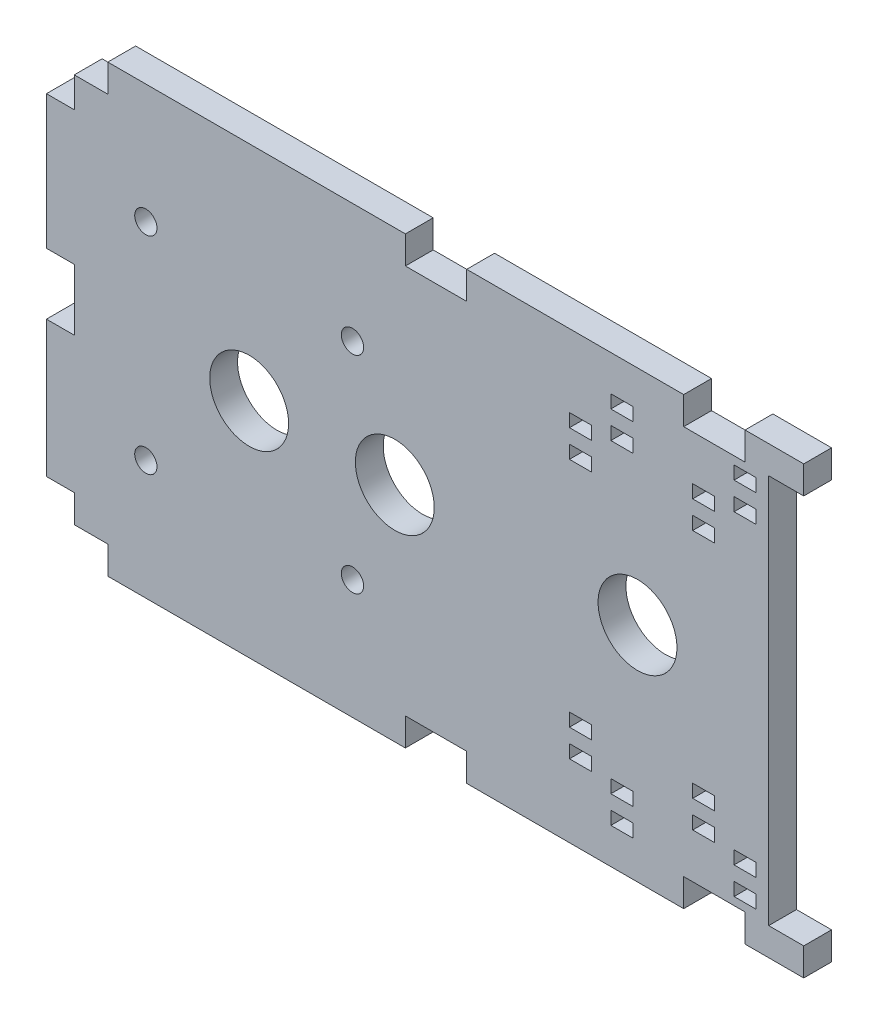
SolidWorks part; units mm, degrees
ref_plane "Front Plane" through (0, 0, 0) normal (0, 0, 1) x (1, 0, 0)
ref_plane "Top Plane" through (0, 0, 0) normal (0, 1, 0) x (1, 0, 0)
ref_plane "Right Plane" through (0, 0, 0) normal (1, 0, 0) x (0, 0, -1)
sketch "Sketch2" plane through (0, 0, 0) normal (0, 0, 1) x (1, 0, 0)
  line L1 (-88.9, -50.8) -> (88.9, -50.8)
  line L2 (-88.9, -50.8) -> (-88.9, 50.8)
  line L3 (-88.9, 50.8) -> (88.9, 50.8)
  line L4 (88.9, -50.8) -> (88.9, 50.8)
  line L5 (-88.9, -50.8) -> (88.9, 50.8) construction
  line L6 (-88.9, 50.8) -> (88.9, -50.8) construction
  point P0 (0, 0)
  dimension "D1" = 101.6
  dimension "D2" = 177.8
extrude "Boss-Extrude3" add sketch "Sketch2" along normal blind 6.35
sketch "Sketch3" plane through (0, 0, 6.35) normal (0, 0, 1) x (1, 0, 0)
  line L0 (-88.9, 0) -> (0, 0) construction
  line L1 (-88.9, 50.8) -> (-88.9, -50.8) construction
  line L2 (0, 0) -> (88.9, 0) construction
  line L3 (88.9, -50.8) -> (88.9, 50.8) construction
  line L4 (0, 50.8) -> (0, -50.8) construction
  line L5 (88.9, 50.8) -> (-88.9, 50.8) construction
  line L6 (-88.9, -50.8) -> (88.9, -50.8) construction
  line L7 (-9.4121, 0) -> (-42.6438, 0) construction
  line L8 (45.9739, 0) -> (-9.4121, 0) construction
  line L9 (-51.6438, 0) -> (-42.6438, -9)
  line L10 (-42.6438, -9) -> (-33.6438, 0)
  line L11 (-33.6438, 0) -> (-42.6438, 9)
  line L12 (-42.6438, 9) -> (-51.6438, 0)
  line L21 (-66.2169, -23.5732) -> (-19.0706, -23.5732)
  line L22 (-66.2169, -23.5732) -> (-66.2169, 23.5732)
  line L23 (-66.2169, 23.5732) -> (-19.0706, 23.5732)
  line L24 (-19.0706, -23.5732) -> (-19.0706, 23.5732)
  line L25 (-66.2169, -23.5732) -> (-19.0706, 23.5732) construction
  line L26 (-66.2169, 23.5732) -> (-19.0706, -23.5732) construction
  line L29 (26.7151, -50.8) -> (26.7151, 50.8) construction
  line L30 (-66.2169, 23.5732) -> (-66.2169, 26.1132) construction
  circle A1 centre (-9.4121, 0) radius 9
  circle A2 centre (-42.6438, 0) radius 9
  circle A3 centre (-66.2169, 23.5732) radius 2.54
  circle A4 centre (-19.0706, 23.5732) radius 2.54
  circle A5 centre (-66.2169, -23.5732) radius 2.54
  circle A6 centre (-19.0706, -23.5732) radius 2.54
  circle A7 centre (45.9739, 0) radius 9
  dimension "D1" = 18
  dimension "D2" = 18
  dimension "D3" = 18
  dimension "D5" = 55.386
  dimension "D6" = 33.2317
  dimension "D7" = 46.2563
extrude "Cut-Extrude1" cut sketch "Sketch3" against normal through all contours A3 | A6 | A5 | A1 | A7 | A2 | A4
sketch "Sketch7" plane through (0, 0, 6.35) normal (0, 0, 1) x (1, 0, 0)
  line L0 (-19.0706, 26.1132) -> (-19.0706, 50.8) construction
  line L1 (88.9, 50.8) -> (-88.9, 50.8) construction
  line L2 (-64.4709, 21.7285) -> (-88.9, 21.7285) construction
  line L3 (-88.9, 50.8) -> (-88.9, -50.8) construction
  line L4 (-88.9, -7) -> (-88.9, 7)
  line L5 (-88.9, 50.8) -> (-74.9, 50.8)
  line L6 (-88.9, 50.8) -> (-88.9, 44.45)
  line L7 (-74.9, 44.45) -> (-82.55, 44.45)
  line L8 (-74.9, 50.8) -> (-74.9, 44.45)
  line L9 (-88.9, -50.8) -> (-74.9, -50.8)
  line L10 (-88.9, -50.8) -> (-88.9, -44.45)
  line L11 (-74.9, -44.45) -> (-82.55, -44.45)
  line L12 (-74.9, -50.8) -> (-74.9, -44.45)
  line L13 (-88.9, -7) -> (-82.55, -7)
  line L14 (-88.9, 7) -> (-82.55, 7)
  line L15 (-82.55, -7) -> (-82.55, 7)
  line L16 (88.9, -50.8) -> (88.9, 50.8) construction
  line L17 (7, 44.45) -> (-7, 44.45)
  line L18 (7, 44.45) -> (7, 50.8)
  line L19 (7, 50.8) -> (-7, 50.8)
  line L20 (-7, 44.45) -> (-7, 50.8)
  line L21 (70.509, 50.8) -> (70.509, 44.45)
  line L22 (83.9, 50.8) -> (83.9, -50.8)
  line L23 (7, -50.8) -> (56.509, -50.8)
  line L24 (56.509, -50.8) -> (70.509, -50.8)
  line L25 (56.509, -50.8) -> (56.509, -44.45)
  line L26 (56.509, -44.45) -> (70.509, -44.45)
  line L27 (70.509, -50.8) -> (70.509, -44.45)
  line L28 (56.509, 44.45) -> (70.509, 44.45)
  line L29 (56.509, 50.8) -> (56.509, 44.45)
  line L30 (56.509, 50.8) -> (70.509, 50.8)
  line L31 (7, 50.8) -> (56.509, 50.8)
  line L32 (83.9, -50.8) -> (88.9, -50.8)
  line L33 (-88.9, -50.8) -> (88.9, -50.8) construction
  line L34 (7, -50.8) -> (-7, -50.8)
  line L35 (7, -50.8) -> (7, -44.45)
  line L36 (-7, -50.8) -> (-7, -44.45)
  line L37 (7, -44.45) -> (-7, -44.45)
  line L38 (-88.9, -7) -> (-88.9, -44.45) construction
  line L39 (88.9, -50.8) -> (88.9, 50.8)
  line L40 (-88.9, -7) -> (-82.55, 7) construction
  line L41 (88.9, 50.8) -> (83.9, 50.8)
  line L42 (83.9, 31.875) -> (75.9, 31.875)
  line L43 (0, 0) -> (-88.9, 0) construction
  line L44 (-82.55, -7) -> (-88.9, 7) construction
  line L45 (75.9, 50.8) -> (75.9, -50.8)
  line L46 (-88.9, 0) -> (88.9, 0) construction
  line L47 (0, 50.8) -> (0, -50.8) construction
  line L48 (0, 50.8) -> (0, 44.45) construction
  line L49 (0, -44.45) -> (0, -50.8) construction
  line L50 (-82.55, 44.45) -> (-82.55, 37.5545)
  line L51 (-82.55, 37.5545) -> (-88.9, 37.5545)
  line L52 (-88.9, 44.45) -> (-88.9, 37.5545)
  line L53 (83.9, 44.45) -> (75.9, 44.45)
  line L54 (-82.55, -44.45) -> (-82.55, -38.1)
  line L55 (-82.55, -38.1) -> (-88.9, -38.1)
  line L56 (-88.9, -44.45) -> (-88.9, -38.1)
  line L57 (75.9, -44.45) -> (83.9, -44.45)
  line L58 (88.9, 16.3459) -> (83.9, 16.3459)
  circle A0 centre (-19.0706, 23.5732) radius 2.54 construction
  circle A2 centre (-66.2169, 23.5732) radius 2.54 construction
  line M8 (88.9, -50.8) -> (88.9, 50.8)
  line M9 (88.9, 50.8) -> (-88.9, 50.8)
  line M10 (-88.9, 50.8) -> (-88.9, -50.8)
  line M11 (-88.9, -50.8) -> (88.9, -50.8)
  dimension "D1" = 24.6868
  dimension "D2" = 24.4291
  dimension "D5" = 6.35
  dimension "D6" = 6.35
  dimension "D7" = 6.35
  dimension "D8" = 49.509
  dimension "D9" = 18.391
extrude "Cut-Extrude2" cut sketch "Sketch7" against normal through all contours L51 L50 L7 L8 M9 M10 | L13 L15 L14 M10 | L54 L55 L12 L11 M10 M11 | L35 L37 L36 M11 | L27 L26 L25 M11 | L29 L28 L21 M9 | L20 L17 L18 M9 | L22 M9 M11 M8 | L42 L45 L22 M11 | L45 L42 L22 M9 | L58 L22 M8 M11
sketch "Sketch9" plane through (0, 0, 6.35) normal (0, 0, 1) x (1, 0, 0)
  line L0 (68.009, -33.397) -> (68.009, -36.397)
  line L1 (39.8884, -33.397) -> (35.4434, -33.397) construction
  line L2 (30.4434, -24.965) -> (30.4434, -27.965)
  line L3 (30.4434, -34.215) -> (35.4434, -34.215)
  line L4 (35.4434, -24.965) -> (35.4434, -27.965)
  line L5 (44.8884, 38.022) -> (39.8884, 38.022) construction
  line L6 (35.4434, -34.215) -> (35.4434, -31.215)
  line L7 (35.4434, -24.965) -> (30.4434, -24.965)
  line L8 (30.4434, -27.965) -> (35.4434, -27.965)
  line L9 (30.4434, -31.215) -> (35.4434, -31.215)
  line L10 (30.4434, -27.965) -> (30.4434, -29.59)
  line L11 (30.4434, -34.215) -> (30.4434, -31.215)
  line L12 (30.4434, -29.59) -> (30.4434, -31.215)
  line L13 (35.4434, -27.965) -> (35.4434, -31.215) construction
  line L14 (35.4434, -31.215) -> (35.498, -31.0212) construction
  line L15 (35.4434, -29.59) -> (58.5634, -29.59) construction
  line L16 (58.5634, -24.965) -> (58.5634, -27.965)
  line L17 (58.5634, -34.215) -> (63.5634, -34.215)
  line L18 (63.5634, -24.965) -> (63.5634, -27.965)
  line L19 (63.5634, -34.215) -> (63.5634, -31.215)
  line L20 (63.5634, -24.965) -> (58.5634, -24.965)
  line L21 (58.5634, -27.965) -> (63.5634, -27.965)
  line L22 (58.5634, -31.215) -> (63.5634, -31.215)
  line L23 (58.5634, -27.965) -> (58.5634, -29.59)
  line L24 (58.5634, -34.215) -> (58.5634, -31.215)
  line L25 (58.5634, -29.59) -> (58.5634, -31.215)
  line L26 (63.5634, -27.965) -> (63.5634, -31.215) construction
  line L27 (63.5634, -31.215) -> (63.618, -31.0212) construction
  line L28 (63.5634, -29.59) -> (58.5634, -29.59) construction
  line L29 (39.8884, 33.397) -> (35.4434, 33.397) construction
  line L30 (63.5629, 29.59) -> (83.9, 29.59) construction
  line L31 (63.5629, 31.215) -> (63.6175, 31.0212) construction
  line L32 (63.5629, 27.965) -> (63.5629, 31.215) construction
  line L33 (35.4429, 29.59) -> (58.5629, 29.59) construction
  line L34 (35.4434, 31.215) -> (35.498, 31.0212) construction
  line L35 (35.4434, 27.965) -> (35.4434, 31.215) construction
  line L36 (58.5629, 29.59) -> (58.5629, 31.215)
  line L37 (58.5629, 34.215) -> (58.5629, 31.215)
  line L38 (58.5629, 27.965) -> (58.5629, 29.59)
  line L39 (58.5629, 31.215) -> (63.5629, 31.215)
  line L40 (58.5629, 27.965) -> (63.5629, 27.965)
  line L41 (63.5629, 24.965) -> (58.5629, 24.965)
  line L42 (63.5629, 34.215) -> (63.5629, 31.215)
  line L43 (63.5629, 24.965) -> (63.5629, 27.965)
  line L44 (58.5629, 34.215) -> (63.5629, 34.215)
  line L45 (58.5629, 24.965) -> (58.5629, 27.965)
  line L46 (30.4434, 29.59) -> (30.4434, 31.215)
  line L47 (30.4434, 34.215) -> (30.4434, 31.215)
  line L48 (30.4434, 27.965) -> (30.4434, 29.59)
  line L49 (30.4434, 31.215) -> (35.4434, 31.215)
  line L50 (30.4434, 27.965) -> (35.4434, 27.965)
  line L51 (35.4434, 24.965) -> (30.4434, 24.965)
  line L52 (35.4434, 34.215) -> (35.4434, 31.215)
  line L53 (35.4434, 24.965) -> (35.4434, 27.965)
  line L54 (73.0084, 38.022) -> (68.0084, 38.022) construction
  line L55 (30.4434, 34.215) -> (35.4434, 34.215)
  line L56 (30.4434, 24.965) -> (30.4434, 27.965)
  line L57 (68.009, -42.647) -> (73.009, -42.647)
  line L58 (73.009, -33.397) -> (73.009, -36.397)
  line L59 (73.009, -42.647) -> (73.009, -39.647)
  line L60 (73.009, -33.397) -> (68.009, -33.397)
  line L61 (68.009, -36.397) -> (73.009, -36.397)
  line L62 (68.009, -39.647) -> (73.009, -39.647)
  line L63 (68.009, -36.397) -> (68.009, -38.022)
  line L64 (68.009, -42.647) -> (68.009, -39.647)
  line L65 (68.009, -38.022) -> (68.009, -39.647)
  line L66 (73.009, -36.397) -> (73.009, -39.647) construction
  line L67 (73.009, -39.647) -> (73.0636, -39.4532) construction
  line L68 (73.009, -38.022) -> (68.009, -38.022) construction
  line L69 (73.0084, 39.647) -> (73.063, 39.4532) construction
  line L70 (73.0084, 36.397) -> (73.0084, 39.647) construction
  line L71 (68.0084, 38.022) -> (68.0084, 39.647)
  line L72 (68.0084, 42.647) -> (68.0084, 39.647)
  line L73 (68.0084, 36.397) -> (68.0084, 38.022)
  line L74 (68.0084, 39.647) -> (73.0084, 39.647)
  line L75 (68.0084, 36.397) -> (73.0084, 36.397)
  line L76 (73.0084, 33.397) -> (68.0084, 33.397)
  line L77 (73.0084, 42.647) -> (73.0084, 39.647)
  line L78 (73.0084, 33.397) -> (73.0084, 36.397)
  line L79 (68.0084, 42.647) -> (73.0084, 42.647)
  line L80 (68.0084, 33.397) -> (68.0084, 36.397)
  line L81 (44.8884, 39.647) -> (44.943, 39.4532) construction
  line L82 (44.8884, 36.397) -> (44.8884, 39.647) construction
  line L83 (39.8884, 38.022) -> (39.8884, 39.647)
  line L84 (39.8884, 42.647) -> (39.8884, 39.647)
  line L85 (39.8884, 36.397) -> (39.8884, 38.022)
  line L86 (39.8884, 39.647) -> (44.8884, 39.647)
  line L87 (39.8884, 36.397) -> (44.8884, 36.397)
  line L88 (44.8884, 33.397) -> (39.8884, 33.397)
  line L89 (44.8884, 42.647) -> (44.8884, 39.647)
  line L90 (44.8884, 33.397) -> (44.8884, 36.397)
  line L91 (39.8884, 42.647) -> (44.8884, 42.647)
  line L92 (39.8884, 33.397) -> (39.8884, 36.397)
  line L93 (68.0084, 34.215) -> (63.5629, 34.215) construction
  line L94 (63.5634, -34.215) -> (68.009, -34.215)
  line L95 (83.9, 44.45) -> (83.9, -44.45) construction
  line L97 (44.8884, -38.022) -> (39.8884, -38.022) construction
  line L98 (44.8884, -36.397) -> (44.943, -36.5908) construction
  line L99 (44.8884, -39.647) -> (44.8884, -36.397) construction
  line L100 (39.8884, -38.022) -> (39.8884, -36.397)
  line L101 (39.8884, -33.397) -> (39.8884, -36.397)
  line L102 (39.8884, -39.647) -> (39.8884, -38.022)
  line L103 (39.8884, -36.397) -> (44.8884, -36.397)
  line L104 (39.8884, -39.647) -> (44.8884, -39.647)
  line L105 (44.8884, -42.647) -> (39.8884, -42.647)
  line L106 (44.8884, -33.397) -> (44.8884, -36.397)
  line L107 (44.8884, -42.647) -> (44.8884, -39.647)
  line L108 (39.8884, -33.397) -> (44.8884, -33.397)
  line L109 (39.8884, -42.647) -> (39.8884, -39.647)
  line L110 (73.0084, 38.022) -> (83.9, 38.022) construction
  line L111 (68.0084, 38.022) -> (44.8884, 38.022) construction
  line L112 (73.0084, 50.8) -> (73.0084, 42.647) construction
  line L113 (83.9, 50.8) -> (70.509, 50.8) construction
  dimension "D1" = 4.4456
  dimension "D2" = 0.818
  dimension "D3" = 20.3371
  dimension "D4" = 0.818
extrude "Cut-Extrude3" cut sketch "Sketch9" against normal through all contours L44 L37 L39 L42 | L55 L47 L49 L52 | L16 L21 L18 L20 | L24 L17 L19 L22 | L2 L8 L4 L7 | L11 L3 L6 L9 | L64 L57 L59 L62 | L79 L72 L74 L77 | L80 L76 L78 L75 | L91 L84 L86 L89 | L92 L88 L90 L87 | L108 L101 L103 L106 | L109 L105 L107 L104 | L40 L43 L41 L45 | L50 L53 L51 L56 | L61 L58 L60 L0
